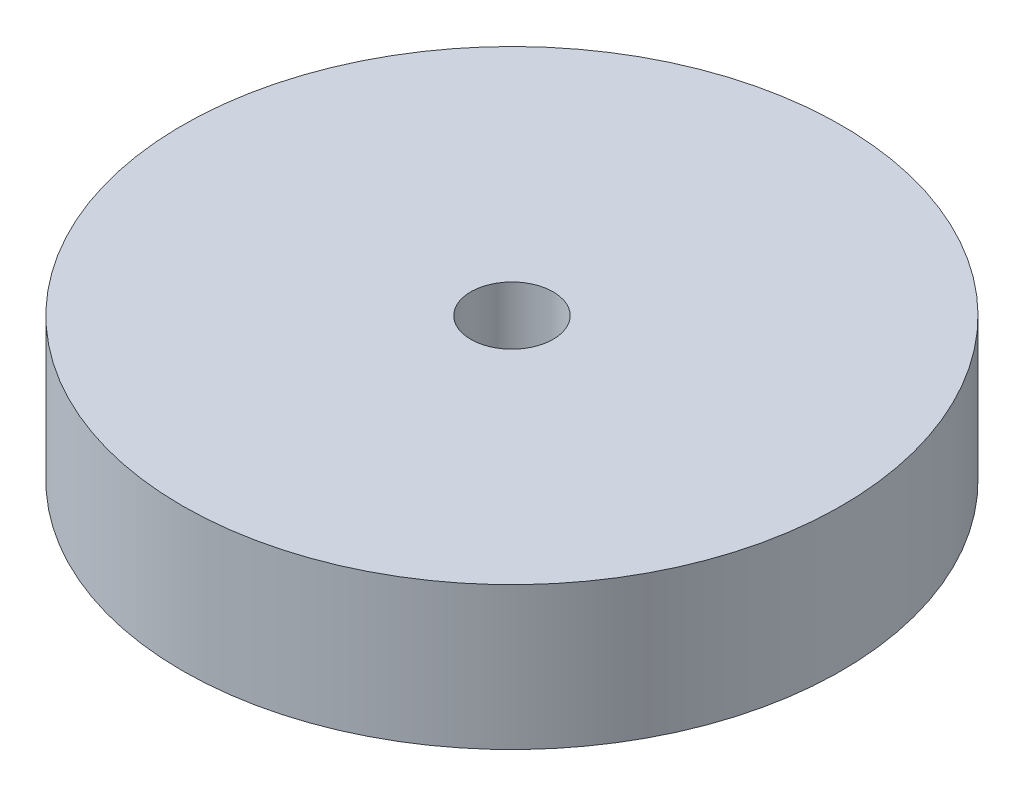
SolidWorks part; units mm, degrees
ref_plane "Front Plane" through (0, 0, 0) normal (0, 0, 1) x (1, 0, 0)
ref_plane "Top Plane" through (0, 0, 0) normal (0, 1, 0) x (1, 0, 0)
ref_plane "Right Plane" through (0, 0, 0) normal (1, 0, 0) x (0, 0, -1)
sketch "Sketch1" plane through (0, 0, 0) normal (0, 1, 0) x (1, 0, 0)
  circle A0 centre (0, 0) radius 300
  circle A1 centre (0, 0) radius 37.5
  dimension "D1" = 600
  dimension "D2" = 75
extrude "Boss-Extrude1" add sketch "Sketch1" along normal blind 130
